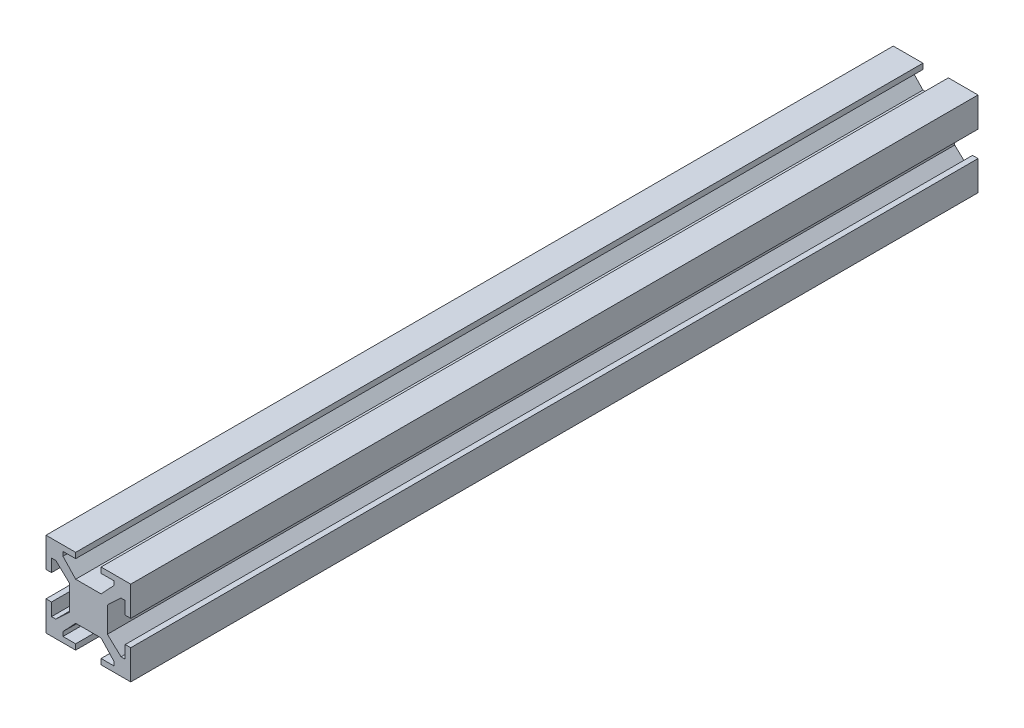
SolidWorks part; units mm, degrees
ref_plane "Front Plane" through (0, 0, 0) normal (0, 0, 1) x (1, 0, 0)
ref_plane "Top Plane" through (0, 0, 0) normal (0, 1, 0) x (1, 0, 0)
ref_plane "Right Plane" through (0, 0, 0) normal (1, 0, 0) x (0, 0, -1)
sketch "Sketch1" plane through (0, 0, 0) normal (0, 0, 1) x (1, 0, 0)
  line L1 (20, 0) -> (13, 0)
  line L2 (20, 0) -> (20, -7)
  line L3 (20, -20) -> (13, -20)
  line L4 (0, 0) -> (0, -7)
  line L6 (18.7, -13) -> (20, -13)
  line L7 (20, -10) -> (14.5, -10) construction
  line L8 (20, -13) -> (20, -20)
  line L9 (20, -7) -> (20, -10) construction
  line L10 (20, -10) -> (20, -13) construction
  line L11 (18.7, -13) -> (18.7, -16)
  line L12 (18.7, -16) -> (17.7, -16)
  line L13 (17.7, -16) -> (14.5, -13)
  line L14 (14.5, -13) -> (14.5, -7)
  line L16 (16, -17.7) -> (13, -14.5)
  line L17 (18.7, -7) -> (20, -7)
  line L18 (18.7, -7) -> (18.7, -4)
  line L19 (18.7, -4) -> (17.7, -4)
  line L20 (17.7, -4) -> (14.5, -7)
  line L21 (0, -10) -> (20, -10) construction
  line L22 (7, -14.5) -> (13, -14.5)
  line L23 (4, -17.7) -> (7, -14.5)
  line L24 (4, -18.7) -> (4, -17.7)
  line L25 (7, -18.7) -> (4, -18.7)
  line L26 (7, -18.7) -> (7, -20)
  line L27 (13, -18.7) -> (13, -20)
  line L28 (13, -18.7) -> (16, -18.7)
  line L29 (16, -18.7) -> (16, -17.7)
  line L30 (2.3, -16) -> (5.5, -13)
  line L31 (5.5, -7) -> (5.5, -13)
  line L32 (2.3, -4) -> (5.5, -7)
  line L33 (1.3, -4) -> (2.3, -4)
  line L34 (1.3, -7) -> (1.3, -4)
  line L35 (1.3, -7) -> (0, -7)
  line L36 (1.3, -13) -> (0, -13)
  line L37 (1.3, -13) -> (1.3, -16)
  line L38 (1.3, -16) -> (2.3, -16)
  line L39 (4, -2.3) -> (7, -5.5)
  line L40 (13, -5.5) -> (7, -5.5)
  line L41 (16, -2.3) -> (13, -5.5)
  line L42 (16, -1.3) -> (16, -2.3)
  line L43 (13, -1.3) -> (16, -1.3)
  line L44 (13, -1.3) -> (13, 0)
  line L45 (7, -1.3) -> (7, 0)
  line L46 (7, -1.3) -> (4, -1.3)
  line L47 (4, -1.3) -> (4, -2.3)
  line L48 (7, 0) -> (0, 0)
  line L49 (13, 0) -> (7, 0) construction
  line L50 (0, -13) -> (0, -20)
  line L51 (0, -7) -> (0, -10) construction
  line L52 (0, -10) -> (0, -13) construction
  line L53 (7, -20) -> (0, -20)
  line L54 (13, -20) -> (7, -20) construction
  point P6 (10, -10)
  point P54 (5.5, -10)
  dimension "D1" = 20
  dimension "D2" = 6
  dimension "D3" = 20
  dimension "D4" = 1.3
  dimension "D5" = 5.5
  dimension "D6" = 6
  dimension "D7" = 1
  dimension "D8" = 3
  dimension "D9" = 4
extrude "Boss-Extrude1" add sketch "Sketch1" along normal blind 200
ref_plane "Plane1" through (0, -10, 0) normal (0, -1, 0) x (-1, 0, 0)
